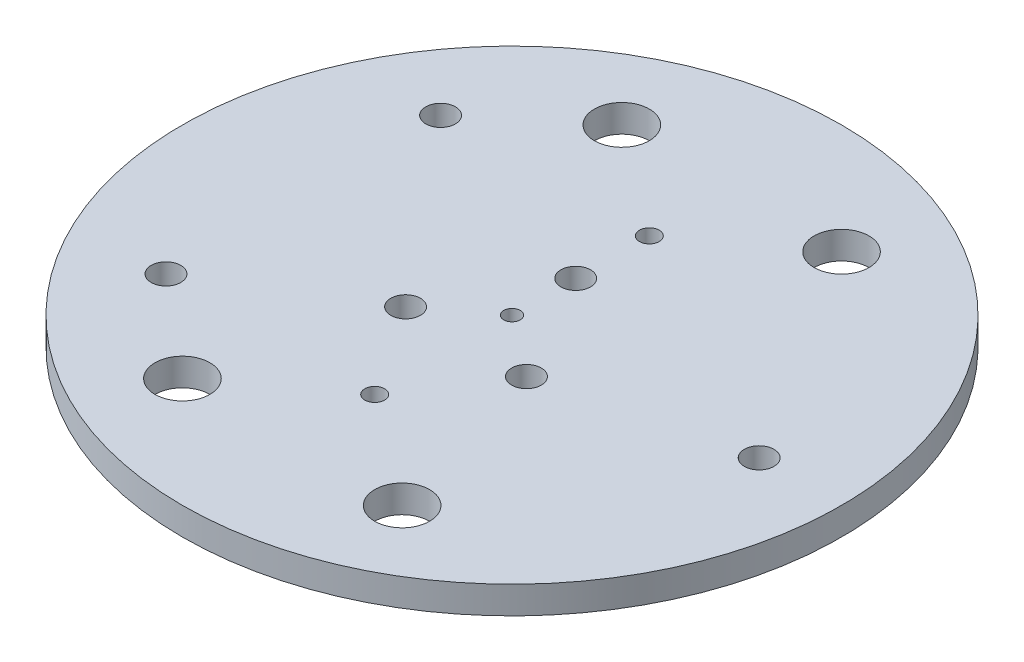
SolidWorks part; units mm, degrees
material "AISI 304"
ref_plane "Front Plane" through (0, 0, 0) normal (0, 0, 1) x (1, 0, 0)
ref_plane "Top Plane" through (0, 0, 0) normal (0, 1, 0) x (1, 0, 0)
ref_plane "Right Plane" through (0, 0, 0) normal (1, 0, 0) x (0, 0, -1)
sketch "Sketch1" plane through (0, 0, 0) normal (0, 1, 0) x (1, 0, 0)
  circle A0 centre (0, 0) radius 76.2
  dimension "D1" = 152.4
extrude "Boss-Extrude1" add sketch "Sketch1" along normal blind 6.35
sketch "Sketch2" plane through (0, 6.35, 0) normal (0, 1, 0) x (1, 0, 0)
  circle A0 centre (0, 0) radius 1.905
  dimension "D1" = 3.81
extrude "Cut-Extrude1" cut sketch "Sketch2" against normal through all
sketch "Sketch3" plane through (0, 6.35, 0) normal (0, 1, 0) x (1, 0, 0)
  circle A0 centre (0, 14.732) radius 3.429
  circle A1 centre (-13.97, -10.6311) radius 3.429
  circle A2 centre (13.97, -10.6311) radius 3.429
  dimension "D4" = 6.858
  dimension "D5" = 6.858
  dimension "D6" = 6.858
  dimension "D1" = 14.732
  dimension "D2" = 13.97
  dimension "D3" = 13.97
  dimension "D7" = 28.956
  dimension "D8" = 28.956
  dimension "D9" = 27.94
extrude "Cut-Extrude2" cut sketch "Sketch3" against normal through all
sketch "Sketch4" plane through (0, 6.35, 0) normal (0, 1, 0) x (1, 0, 0)
  circle A0 centre (-25.4, -50.8) radius 6.35
  circle A1 centre (25.4, -50.8) radius 6.35
  circle A5 centre (0, 0) radius 1.905 construction
  dimension "D1" = 50.8
  dimension "D2" = 25.4
  dimension "D3" = 12.7
  dimension "D4" = 12.7
  dimension "D5" = 50.8
  dimension "D6" = 25.4
extrude "Cut-Extrude3" cut sketch "Sketch4" against normal through all
sketch "Sketch5" plane through (0, 6.35, 0) normal (0, 1, 0) x (1, 0, 0)
  circle A0 centre (-25.4, 50.8) radius 6.35
  circle A1 centre (25.4, 50.8) radius 6.35
  circle A2 centre (0, 14.732) radius 3.429 construction
  circle A3 centre (0, 0) radius 1.905 construction
  dimension "D2" = 50.8
  dimension "D3" = 12.7
  dimension "D4" = 12.7
  dimension "D1" = 50.8
  dimension "D5" = 25.4
  dimension "D6" = 25.4
extrude "Cut-Extrude4" cut sketch "Sketch5" against normal through all
sketch "Sketch7" plane through (0, 6.35, 0) normal (0, 1, 0) x (1, 0, 0)
  circle A0 centre (0, 46.99) radius 2.54
  circle A1 centre (0, -46.99) radius 2.54
  circle A2 centre (0, 0) radius 1.905 construction
  circle A3 centre (25.4, -50.8) radius 6.35 construction
  circle A4 centre (25.4, 50.8) radius 6.35 construction
  dimension "D1" = 5.08
  dimension "D2" = 5.08
  dimension "D3" = 46.99
  dimension "D4" = 46.99
  dimension "D5" = 25.4
  dimension "D6" = 25.4
extrude "Cut-Extrude6" cut sketch "Sketch7" against normal through all
sketch "Sketch8" plane through (0, 6.35, 0) normal (0, 1, 0) x (1, 0, 0)
  circle A0 centre (57.15, 0) radius 3.429
  circle A1 centre (0, 0) radius 1.905 construction
  circle A2 centre (0, -46.99) radius 2.54 construction
  dimension "D1" = 6.858
  dimension "D2" = 57.15
  dimension "D3" = 46.99
extrude "Cut-Extrude7" cut sketch "Sketch8" against normal through all
sketch "Sketch9" plane through (0, 6.35, 0) normal (0, 1, 0) x (1, 0, 0)
  line L1 (-48.26, 31.75) -> (-48.26, -31.75)
  circle A1 centre (0, 0) radius 1.905 construction
  circle A2 centre (-48.26, -31.75) radius 3.429
  circle A3 centre (-48.26, 31.75) radius 3.429
  dimension "D1" = 48.26
  dimension "D2" = 6.858
  dimension "D3" = 6.858
  dimension "D4" = 63.5
  dimension "D5" = 31.75
extrude "Cut-Extrude8" cut sketch "Sketch9" against normal through all
sketch "Sketch10" plane through (0, 6.35, 0) normal (0, 1, 0) x (1, 0, 0)
  circle A0 centre (0, 46.99) radius 2.54
  circle A1 centre (0, -46.99) radius 2.54
extrude "Boss-Extrude2" add sketch "Sketch10" against normal blind 6.35
sketch "Sketch11" plane through (0, 6.35, 0) normal (0, 1, 0) x (1, 0, 0)
  circle A0 centre (0, -31.75) radius 2.286
  circle A1 centre (0, 31.75) radius 2.286
  circle A2 centre (0, 0) radius 1.905 construction
  circle A3 centre (-25.4, -50.8) radius 6.35 construction
  circle A5 centre (25.4, 50.8) radius 6.35 construction
  dimension "D2" = 31.75
  dimension "D3" = 4.572
  dimension "D4" = 4.572
  dimension "D5" = 25.4
  dimension "D1" = 31.75
  dimension "D6" = 25.4
extrude "Cut-Extrude9" cut sketch "Sketch11" against normal through all
